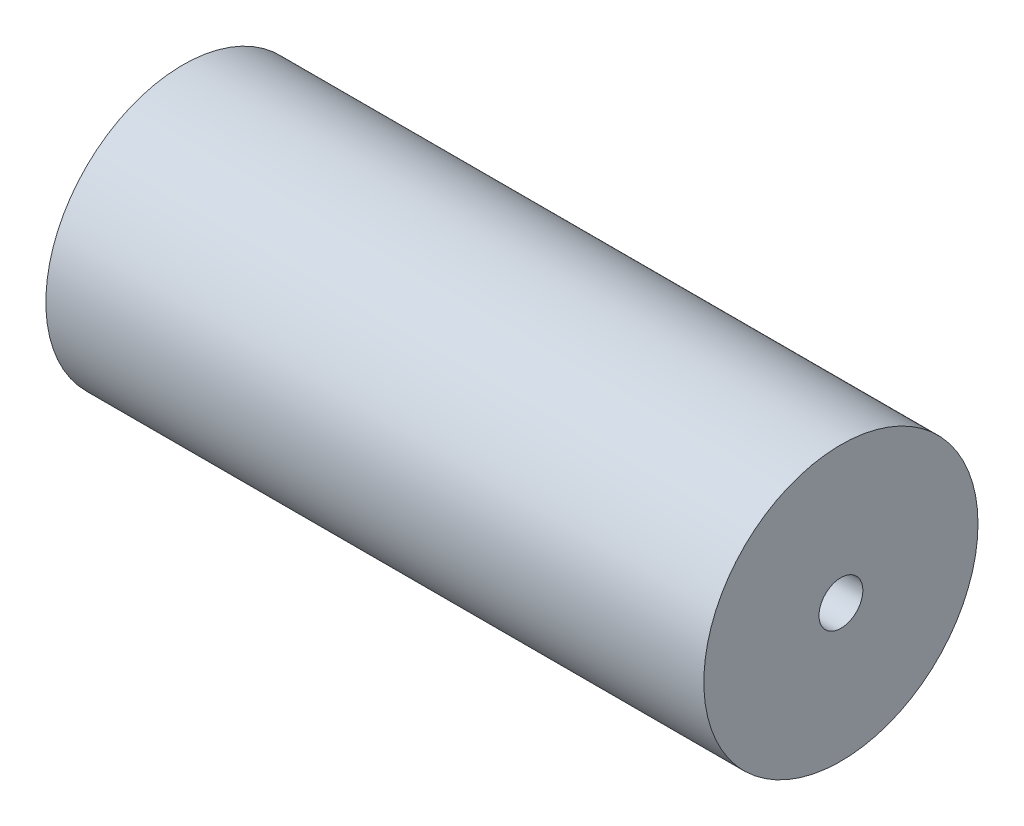
SolidWorks part; units mm, degrees
ref_plane "Front Plane" through (0, 0, 0) normal (0, 0, 1) x (1, 0, 0)
ref_plane "Top Plane" through (0, 0, 0) normal (0, 1, 0) x (1, 0, 0)
ref_plane "Right Plane" through (0, 0, 0) normal (1, 0, 0) x (0, 0, -1)
sketch "Sketch1" plane through (0, 0, 0) normal (1, 0, 0) x (0, 0, -1)
  circle A0 centre (0, 0) radius 25
  dimension "D1" = 50
extrude "Boss-Extrude1" add sketch "Sketch1" along normal mid plane 120
sketch "Sketch2" plane through (60, 0, 0) normal (1, 0, 0) x (0, 0, -1)
  circle A0 centre (0, 0) radius 4
  dimension "D1" = 8
extrude "Cut-Extrude1" cut sketch "Sketch2" against normal through all
